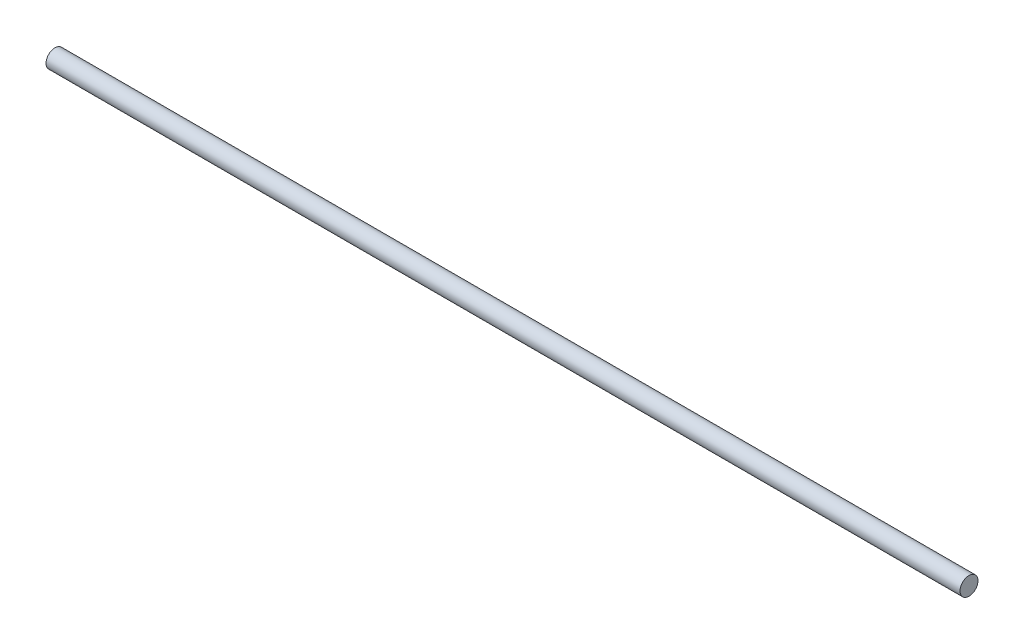
SolidWorks part; units mm, degrees
ref_plane "Front Plane" through (0, 0, 0) normal (0, 0, 1) x (1, 0, 0)
ref_plane "Top Plane" through (0, 0, 0) normal (0, 1, 0) x (1, 0, 0)
ref_plane "Right Plane" through (0, 0, 0) normal (1, 0, 0) x (0, 0, -1)
sketch "Sketch1" plane through (0, 0, 0) normal (1, 0, 0) x (0, 0, -1)
  circle A0 centre (0, 0) radius 6
extrude "Boss-Extrude1" add sketch "Sketch1" along normal mid plane 609.6
